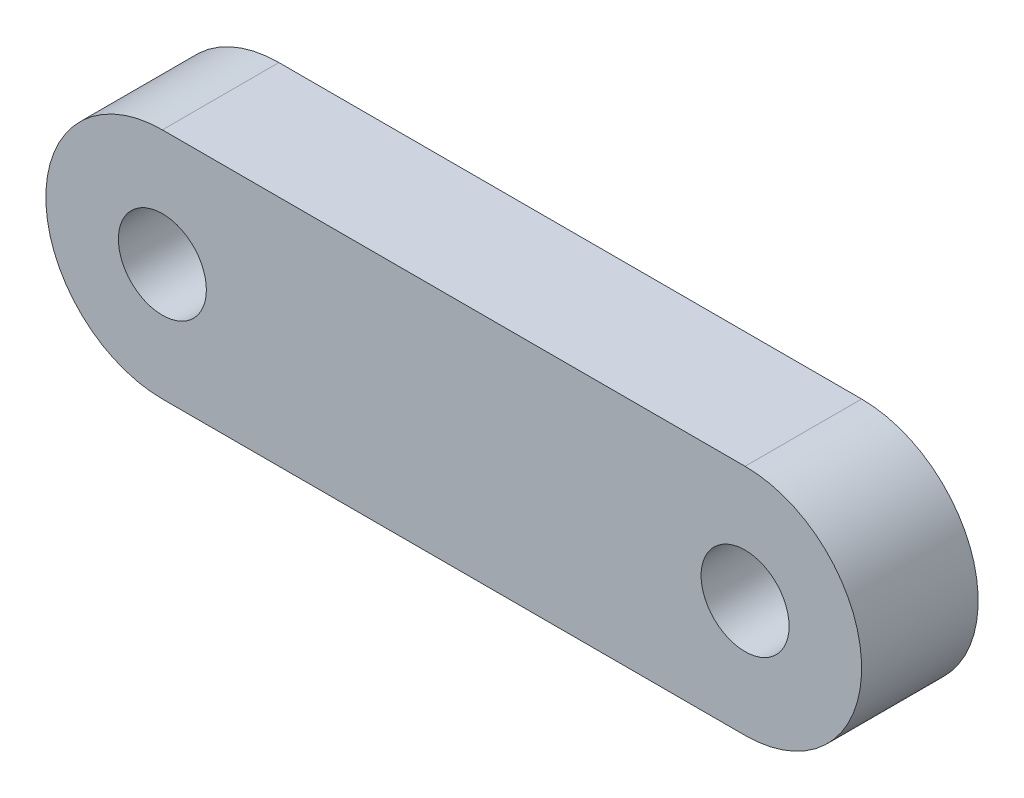
SolidWorks part; units mm, degrees
material "PET"
ref_plane "Front Plane" through (0, 0, 0) normal (0, 0, 1) x (1, 0, 0)
ref_plane "Top Plane" through (0, 0, 0) normal (0, 1, 0) x (1, 0, 0)
ref_plane "Right Plane" through (0, 0, 0) normal (1, 0, 0) x (0, 0, -1)
sketch "Sketch1" plane through (0, 0, 0) normal (0, 0, 1) x (1, 0, 0)
  line L2 (0, 0) -> (2.005, 0) construction
  line L3 (0, 4) -> (20, 4)
  line L4 (0, -4) -> (20, -4)
  line L5 (18.49, 0) -> (20, 0) construction
  circle A4 centre (0, 0) radius 1.51
  circle A5 centre (20, 0) radius 1.51
  arc A6 (0, 4) -> (0, -4) centre (0, 0) ccw
  arc A7 (20, -4) -> (20, 4) centre (20, 0) ccw
extrude "Boss-Extrude1" add sketch "Sketch1" along normal blind 4
